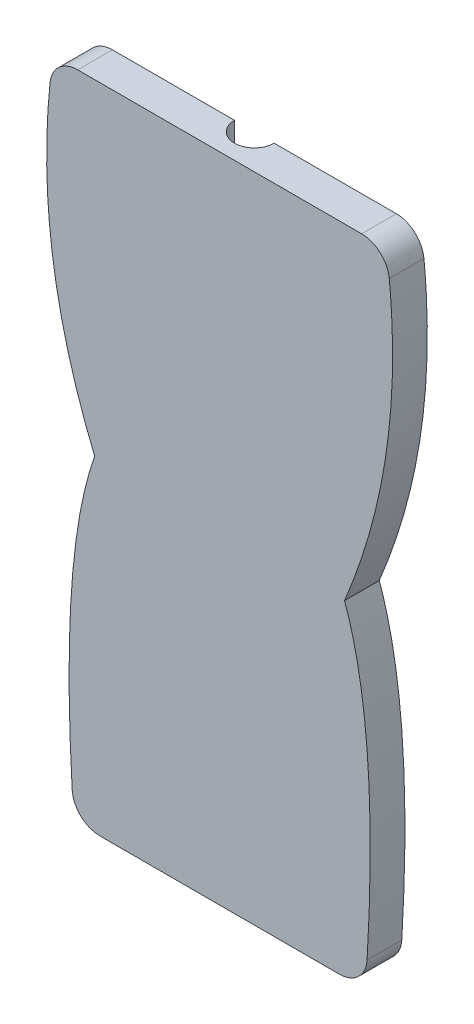
SolidWorks part; units mm, degrees
ref_plane "Front Plane" through (0, 0, 0) normal (0, 0, 1) x (1, 0, 0)
ref_plane "Top Plane" through (0, 0, 0) normal (0, 1, 0) x (1, 0, 0)
ref_plane "Right Plane" through (0, 0, 0) normal (1, 0, 0) x (0, 0, -1)
sketch "Sketch1" plane through (0, 0, 0) normal (0, 0, 1) x (1, 0, 0)
  line L0 (0, 0) -> (0, 470) construction
  line L1 (0, 235) -> (90, 235) construction
  line L2 (0, 235) -> (-90, 235) construction
  line L3 (0, 470) -> (102.3045, 470)
  line L4 (0, 470) -> (-102.3045, 470)
  line L5 (0, 0) -> (-86.2649, 0)
  line L6 (0, 0) -> (86.2649, 0)
  arc A0 (-106.2299, 18.8173) -> (-86.2649, 0) centre (-86.2649, 20) ccw
  arc A1 (86.2649, 0) -> (106.2299, 18.8173) centre (86.2649, 20) ccw
  arc A2 (-102.3045, 470) -> (-122.1989, 452.0524) centre (-102.3045, 450) ccw
  arc A3 (122.1989, 452.0524) -> (102.3045, 470) centre (102.3045, 450) ccw
  spline S0 degree 3 poles (-122.1989, 452.0524) (-126.0571, 414.6538) (-124.5487, 341.0799) (-104.5911, 269.9522) (-90, 235) knots 0.073882 0.073882 0.073882 0.073882 0.536941 1 1 1 1
  spline S1 degree 3 poles (-90, 235) (-98.3104, 211.9025) (-109.3258, 152.7745) (-109.1303, 67.7807) (-106.2299, 18.8173) knots 0 0 0 0 0.470365 0.94073 0.94073 0.94073 0.94073
  spline S2 degree 3 poles (90, 235) (98.3104, 211.9025) (109.3258, 152.7745) (109.1303, 67.7807) (106.2299, 18.8173) knots 0 0 0 0 0.470365 0.94073 0.94073 0.94073 0.94073
  spline S3 degree 3 poles (122.1989, 452.0524) (126.0571, 414.6538) (124.5487, 341.0799) (104.5911, 269.9522) (90, 235) knots 0.073882 0.073882 0.073882 0.073882 0.536941 1 1 1 1
  dimension "D1" = 20
  dimension "D2" = 20
  dimension "D3" = 20
  dimension "D4" = 20
extrude "Boss-Extrude1" add sketch "Sketch1" along normal blind 25
sketch "Sketch2" plane through (0, 0, 0) normal (0, 1, 0) x (1, 0, 0)
  circle A0 centre (0, 0) radius 14.285
extrude "Cut-Extrude1" cut sketch "Sketch2" along normal through all
